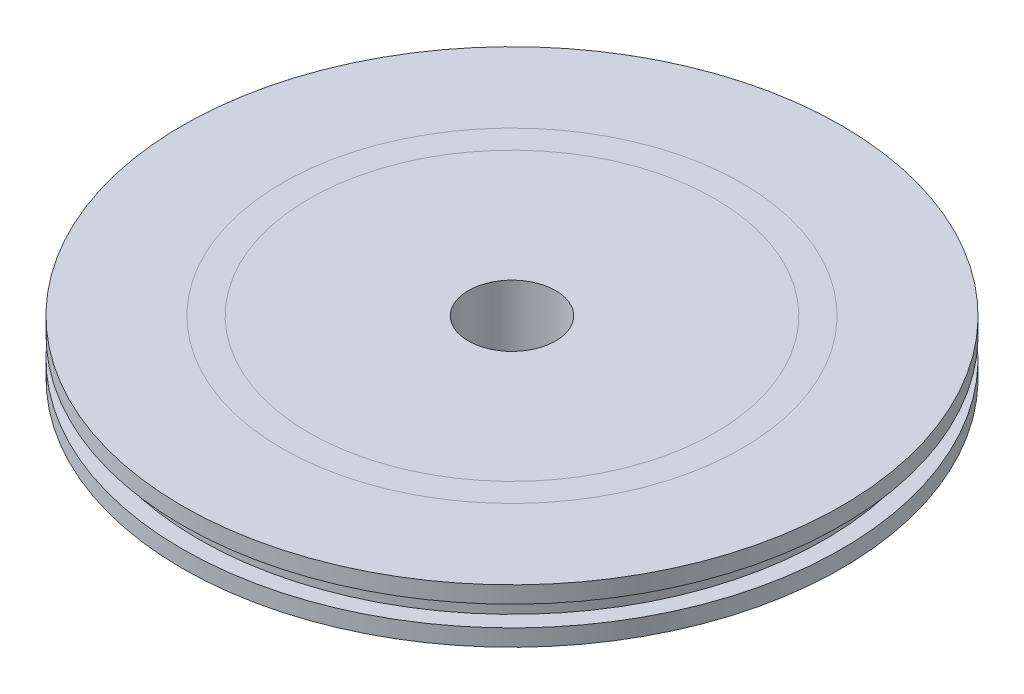
SolidWorks part; units mm, degrees
material "6061-T6 (SS)"
ref_plane "X-Y Datum" through (0, 0, 0) normal (0, 0, 1) x (1, 0, 0)
ref_plane "X-Z Datum" through (0, 0, 0) normal (0, 1, 0) x (1, 0, 0)
ref_plane "Y-Z Datum" through (0, 0, 0) normal (1, 0, 0) x (0, 0, -1)
sketch "Sketch1" plane through (0, 0, 0) normal (1, 0, 0) x (0, 0, -1)
  line L0 (0, 0) -> (0, -32027.2037) construction
  line L1 (0, 0) -> (0, -5.08)
  line L2 (0, -5.08) -> (-30.9499, -5.08)
  line L3 (-30.9499, -5.08) -> (-30.9499, -3.5052)
  line L4 (-30.9499, -3.5052) -> (-29.3878, -3.5052)
  line L5 (-29.3878, -3.5052) -> (-29.3878, -1.5748)
  line L6 (-29.3878, -1.5748) -> (-30.9499, -1.5748)
  line L7 (-30.9499, -1.5748) -> (-30.9499, 0)
  line L8 (-30.9499, 0) -> (0, 0)
  dimension "D1" = 61.8998
  dimension "D2" = 5.08
  dimension "D3" = 1.9304
  dimension "D5" = 58.7756
revolve "Revolve1" add sketch "Sketch1" angle 360 about L0
sketch "Sketch2" plane through (0, 0, 0) normal (0, 1, 0) x (1, 0, 0)
  circle A0 centre (0, 0) radius 19.05
  dimension "D1" = 38.1
split line "Split Line1"
sketch "Sketch3" plane through (0, 0, 0) normal (0, 1, 0) x (1, 0, 0)
  circle A0 centre (0, 0) radius 21.59
  dimension "D1" = 43.18
split line "Split Line2"
hole_wizard "Ø10.0mm Dowel Hole1" positions "Sketch4" profile "Sketch5" hole size "Ø10.0" standard "ANSI Metric"
sketch "Sketch4" plane through (0, 0, 0) normal (0, 1, 0) x (1, 0, 0)
  point P0 (0, 0)
sketch "Sketch5" plane through (0, 0, 0) normal (1, 0, 0) x (0, 0, 1)
  line L0 (0, 0) -> (0, 5.08)
  line L1 (0, 5.08) -> (5, 5.08)
  line L2 (5, 5.08) -> (5, 0)
  line L5 (5, 0) -> (0, 0)
  line L11 (0, -6.35) -> (0, 107.95) construction
  dimension "Thru Hole Dia." = 10
  dimension "Thru Hole Depth" = 5.08
sketch "Sketch6" plane through (0, -5.08, 0) normal (0, -1, 0) x (1, 0, 0)
  circle A0 centre (0, 0) radius 4.1021
  dimension "D1" = 8.2042
extrude "5/16 Close Fit hole" cut sketch "Sketch6" against normal through all
sketch "Sketch7" plane through (0, -5.08, 0) normal (0, -1, 0) x (1, 0, 0)
  circle A0 centre (0, 0) radius 22.86
  circle A1 centre (0, 0) radius 4.1021
  circle A2 centre (0, 0) radius 4.1021 construction
  dimension "D1" = 45.72
extrude "Boss-Extrude1" add sketch "Sketch7" along normal blind 1.016
